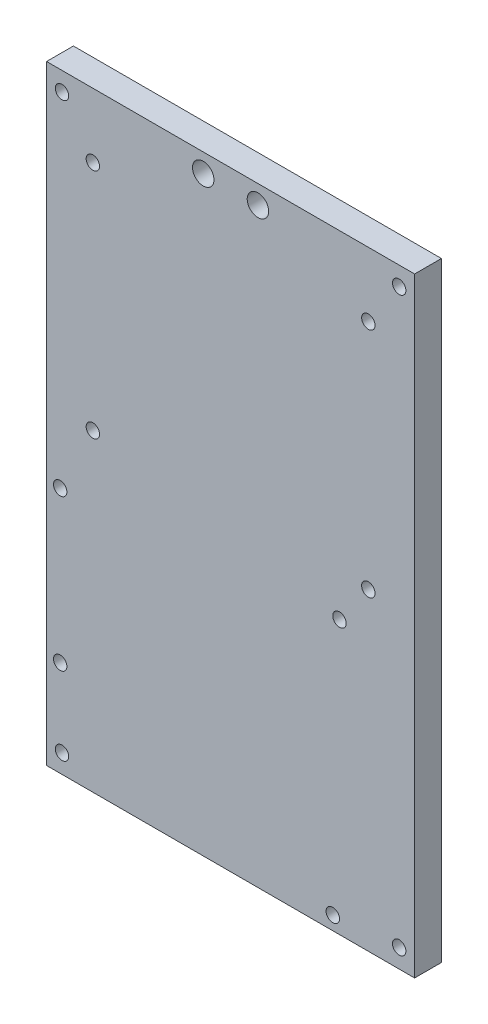
SolidWorks part; units mm, degrees
ref_plane "Front" through (0, 0, 0) normal (0, 0, 1) x (1, 0, 0)
ref_plane "Top" through (0, 0, 0) normal (0, 1, 0) x (1, 0, 0)
ref_plane "Right" through (0, 0, 0) normal (1, 0, 0) x (0, 0, -1)
sketch "arduinoOutline" plane through (0, 0, 0) normal (0, 0, 1) x (1, 0, 0)
  line L0 (0, 32.73) -> (2.54, 35.27) construction
  line L2 (0, 0) -> (0, 32.73) construction
  line L5 (2.54, 35.27) -> (2.54, 36.81) construction
  line L6 (3.54, 37.81) -> (67.6, 37.81) construction
  line L7 (68.6, 36.81) -> (68.6, -14.59) construction
  line L8 (67.6, -15.59) -> (4.06, -15.59) construction
  line L9 (4.06, -15.59) -> (2.54, -14.07) construction
  line L10 (2.54, -14.07) -> (2.54, -2.54) construction
  line L11 (2.54, -2.54) -> (0, 0) construction
  arc A0 (2.54, 36.81) -> (3.54, 37.81) centre (3.54, 36.81) cw construction
  arc A1 (68.6, -14.59) -> (67.6, -15.59) centre (67.6, -14.59) cw construction
  arc A2 (67.6, 37.81) -> (68.6, 36.81) centre (67.6, 36.81) cw construction
  point P8 (2.54, 37.81)
  point P13 (68.6, -15.59)
  point P16 (68.6, 37.81)
  dimension "D6" = 1
  dimension "D9" = 1
  dimension "D10" = 1
  dimension "D1" = 32.73
  dimension "D2" = 135
  dimension "D3" = 3.5921
  dimension "D4" = 2.54
  dimension "D5" = 66.06
  dimension "D7" = 53.4
  dimension "D8" = 64.54
  dimension "D11" = 135
  dimension "D12" = 2.1496
  dimension "D13" = 11.53
  dimension "D14" = 135
  dimension "D15" = 3.5921
sketch "arduinoMountingHolesSketch" plane through (0, 0, 0) normal (0, 0, 1) x (1, 0, 0)
  line L0 (0, 0) -> (0, 32.73) construction
  line L1 (67.6, -15.59) -> (4.06, -15.59) construction
  line L2 (3.54, 37.81) -> (67.6, 37.81) construction
  line L3 (68.6, 36.81) -> (68.6, -14.59) construction
  circle A0 centre (2.54, 2.28) radius 1.25
  circle A1 centre (2.54, 30.45) radius 1.25
  circle A2 centre (54.6, 35.27) radius 1.25
  circle A3 centre (53.35, -13.05) radius 1.25
  dimension "D9" = 2.5
  dimension "D1" = 2.54
  dimension "D2" = 17.87
  dimension "D3" = 2.54
  dimension "D4" = 7.36
  dimension "D5" = 2.54
  dimension "D6" = 14
  dimension "D7" = 2.54
  dimension "D8" = 15.25
sketch "9VbatteryMountingHolesSketch" plane through (0, 0, 0) normal (0, 0, 1) x (1, 0, 0)
  line L0 (0, 16.365) -> (68.6, 16.365) construction
  line L1 (4.875, 40.31) -> (63.725, 40.31) construction
  line L2 (4.875, 40.31) -> (4.875, 88.56) construction
  line L3 (4.875, 88.56) -> (63.725, 88.56) construction
  line L4 (63.725, 40.31) -> (63.725, 88.56) construction
  line L5 (0, 0) -> (0, 32.73) construction
  line L6 (68.6, 36.81) -> (68.6, -14.59) construction
  line L7 (34.3, 40.31) -> (34.3, 88.56) construction
  line L8 (4.875, 64.435) -> (63.725, 64.435) construction
  line L10 (3.54, 37.81) -> (67.6, 37.81) construction
  circle A0 centre (8.625, 86.06) radius 1.25
  circle A1 centre (59.975, 86.06) radius 1.25
  circle A2 centre (8.625, 42.81) radius 1.25
  circle A3 centre (59.975, 42.81) radius 1.25
  point P4 (34.3, 16.365)
  point P5 (34.3, 88.56)
  point P24 (34.3, 43.588)
  dimension "D3" = 2.5
  dimension "D1" = 48.25
  dimension "D2" = 58.85
  dimension "D4" = 2.5
  dimension "D5" = 3.75
  dimension "D6" = 2.5
sketch "legBracketMountingHolesSketch" plane through (0, 0, 0) normal (0, 0, 1) x (1, 0, 0)
  line L0 (34.3, 91.06) -> (34.3, 98.06) construction
  line L1 (24.1051, 98.06) -> (44.4949, 98.06) construction
  line L2 (24.1051, 98.06) -> (24.1051, 91.06) construction
  line L3 (24.1051, 91.06) -> (44.4949, 91.06) construction
  line L4 (44.4949, 98.06) -> (44.4949, 91.06) construction
  circle A0 centre (29.2026, 94.56) radius 2
  circle A1 centre (39.3974, 94.56) radius 2
  point P4 (24.1051, 94.56)
  point P5 (34.3, 98.06)
  point P13 (34.3, 101.6075)
  dimension "D4" = 4
  dimension "D1" = 7
  dimension "D2" = 20.3898
  dimension "D3" = 2.5
  dimension "D5" = 5.0974
sketch "backsideMountingHolesSketch" plane through (0, 0, 0) normal (0, 0, 1) x (1, 0, 0)
  line L0 (0, 41.235) -> (68.6, 41.235) construction
  line L9 (0, 0) -> (0, 32.73) construction
  line L10 (34.3, 40.31) -> (34.3, 88.56) construction
  line L11 (68.6, 36.81) -> (68.6, -14.59) construction
  line L12 (24.1051, 98.06) -> (44.4949, 98.06) construction
  line L13 (4.875, 88.56) -> (63.725, 88.56) construction
  line L14 (4.875, 40.31) -> (4.875, 88.56) construction
  circle A1 centre (2.875, 94.56) radius 1.25
  circle A5 centre (65.725, 94.56) radius 1.25
  circle A6 centre (65.725, -12.09) radius 1.25
  circle A7 centre (2.875, -12.09) radius 1.25
  point P6 (0, 0)
  point P7 (2.8495, 94.6126)
  dimension "D1" = 2.5
  dimension "D2" = 56.825
  dimension "D3" = 6
  dimension "D4" = 2
sketch "Sketch1" plane through (0, 0, 0) normal (0, 0, 1) x (1, 0, 0)
  line L0 (67.6, -15.59) -> (4.06, -15.59) construction
  line L1 (0, 98.06) -> (68.6, 98.06)
  line L2 (0, 98.06) -> (0, -15.59)
  line L3 (0, -15.59) -> (68.6, -15.59)
  line L4 (68.6, 98.06) -> (68.6, -15.59)
  line L5 (0, 0) -> (0, 32.73) construction
  line L6 (68.6, 36.81) -> (68.6, -14.59) construction
  line L9 (24.1051, 98.06) -> (44.4949, 98.06) construction
extrude "bracketBase" add sketch "Sketch1" along normal blind 5
extrude "arduinoMountingHoles" cut sketch "arduinoMountingHolesSketch" against normal through all and the other way blind 22
extrude "9VbatteryMountingHoles" cut sketch "9VbatteryMountingHolesSketch" along normal blind 20
extrude "legBracketMountingHoles" cut sketch "legBracketMountingHolesSketch" along normal blind 13
extrude "backsideMountingHoles" cut sketch "backsideMountingHolesSketch" along normal blind 24
equation "\"D2@backsideMountingHolesSketch\"=113.65mm/2"
